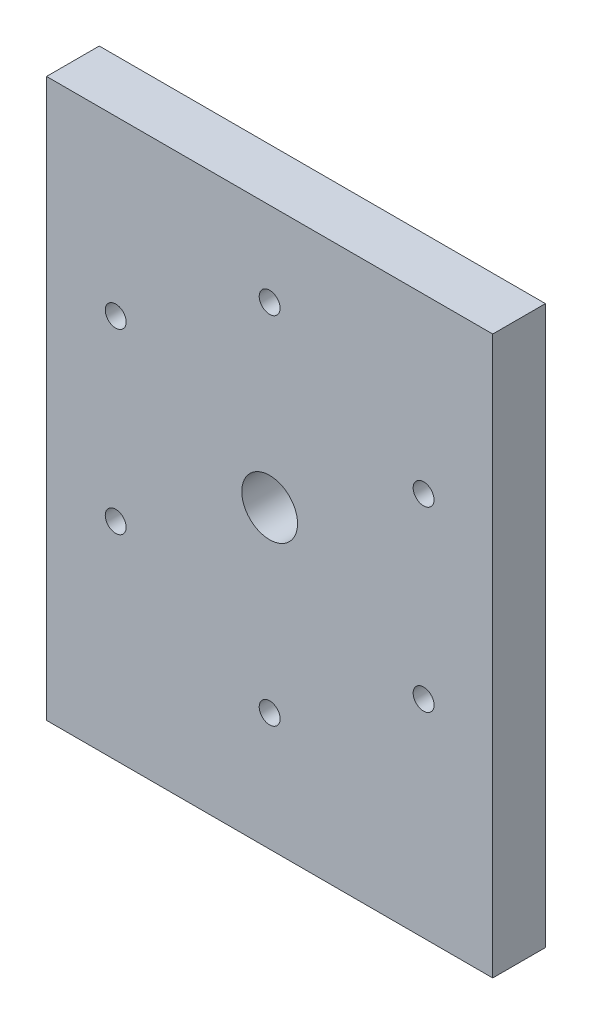
SolidWorks part; units mm, degrees
material "Acrylic (Medium-high impact)"
ref_plane "Front Plane" through (0, 0, 0) normal (0, 0, 1) x (1, 0, 0)
ref_plane "Top Plane" through (0, 0, 0) normal (0, 1, 0) x (1, 0, 0)
ref_plane "Right Plane" through (0, 0, 0) normal (1, 0, 0) x (0, 0, -1)
sketch "Sketch1" plane through (0, 0, 0) normal (0, 0, 1) x (1, 0, 0)
  line L0 (34.1802, 50.5429) -> (34.1802, 53.0508) construction
  line L1 (-50.8, 127) -> (50.8, 127)
  line L2 (-50.8, 127) -> (-50.8, 0)
  line L3 (-50.8, 0) -> (50.8, 0)
  line L4 (50.8, 127) -> (50.8, 0)
  circle A0 centre (0, 67.375) radius 6.35
  circle A7 centre (0, 67.375) radius 38.1 construction
  dimension "D1" = 127
  dimension "D3" = 12.7
  dimension "D12" = 76.2
  dimension "D2" = 101.6
  dimension "D5" = 67.375
extrude "Boss-Extrude1" add sketch "Sketch1" along normal blind 12
sketch "Sketch2" plane through (0, 0, 0) normal (0, 0, -1) x (-1, 0, 0)
  circle A0 centre (0, 107.8562) radius 2.3812
  circle A1 centre (0, 67.375) radius 38.1 construction
  dimension "D1" = 4.7625
extrude "Cut-Extrude1" cut sketch "Sketch2" against normal through all
pattern_circular "CirPattern1" count 6 every 60 about axis through (0, 67.375, 0) along (0, 0, 1) of "Cut-Extrude1"
sketch "Sketch3" plane through (0, 0, 0) normal (0, -1, 0) x (1, 0, 0)
  line L0 (31.75, 6) -> (-31.75, 6) construction
  line L2 (0, 0) -> (0, 12) construction
  line L3 (-50.8, 12) -> (50.8, 12) construction
  circle A0 centre (31.75, 6) radius 2.3812
  circle A1 centre (0, 6) radius 2.3813
  circle A2 centre (-31.75, 6) radius 2.3813
  point P4 (0, 0)
  point P9 (0, 6)
  dimension "D2" = 4.7625
  dimension "D1" = 31.75
extrude "Cut-Extrude2" cut sketch "Sketch3" against normal blind 12.7
